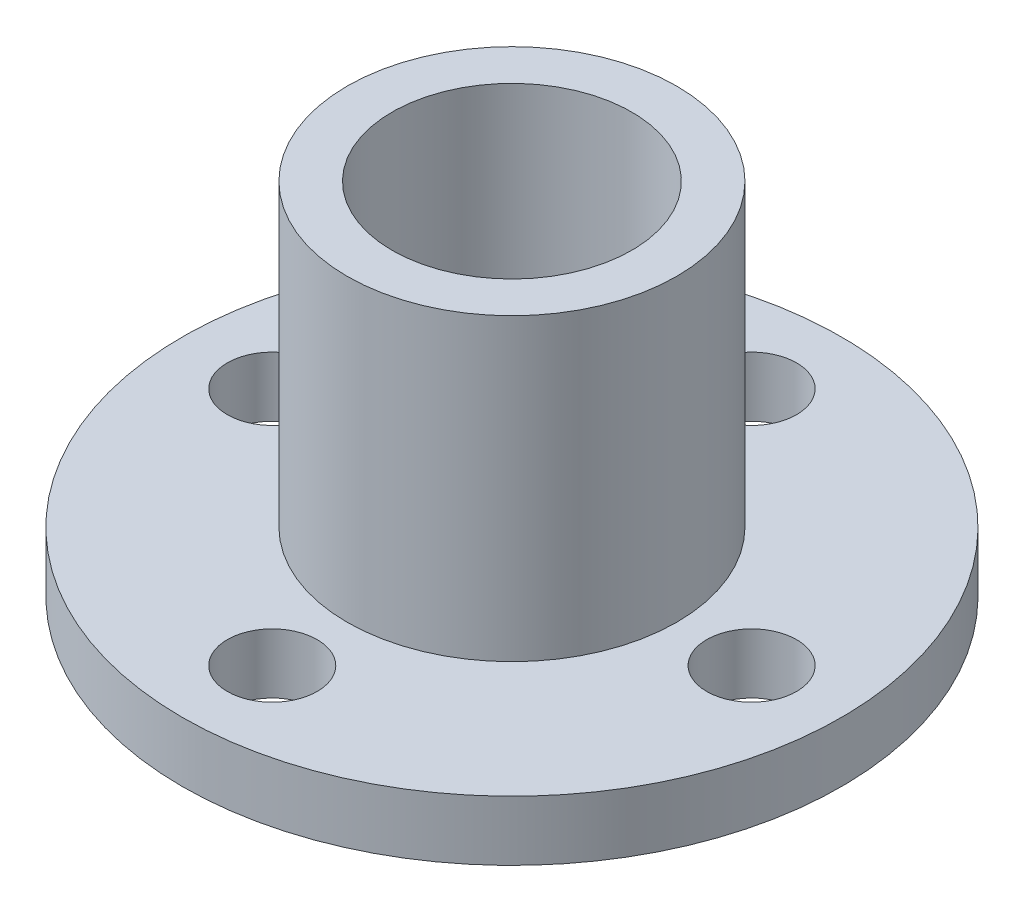
SolidWorks part; units mm, degrees
ref_plane "Front Plane" through (0, 0, 0) normal (0, 0, 1) x (1, 0, 0)
ref_plane "Top Plane" through (0, 0, 0) normal (0, 1, 0) x (1, 0, 0)
ref_plane "Right Plane" through (0, 0, 0) normal (1, 0, 0) x (0, 0, -1)
sketch "Sketch1" plane through (0, 0, 0) normal (0, 1, 0) x (1, 0, 0)
  circle A0 centre (0, 0) radius 11
  circle A1 centre (0, 0) radius 4
  dimension "D1" = 22
  dimension "D2" = 8
extrude "Boss-Extrude1" add sketch "Sketch1" along normal blind 2
sketch "Sketch2" plane through (0, 2, 0) normal (0, 1, 0) x (1, 0, 0)
  circle A0 centre (8, 0) radius 1.5
  circle A1 centre (-8, 0) radius 1.5
  circle A2 centre (0, 8) radius 1.5
  circle A3 centre (0, -8) radius 1.5
  dimension "D2" = 3
  dimension "D4" = 3
  dimension "D6" = 3
  dimension "D8" = 3
  dimension "D1" = 8
  dimension "D3" = 8
  dimension "D5" = 8
  dimension "D7" = 8
extrude "Cut-Extrude1" cut sketch "Sketch2" against normal blind 2
sketch "Sketch3" plane through (0, 2, 0) normal (0, 1, 0) x (1, 0, 0)
  circle A0 centre (0, 0) radius 4
  circle A1 centre (0, 0) radius 5.5
  dimension "D1" = 11
extrude "Boss-Extrude2" add sketch "Sketch3" along normal blind 10
